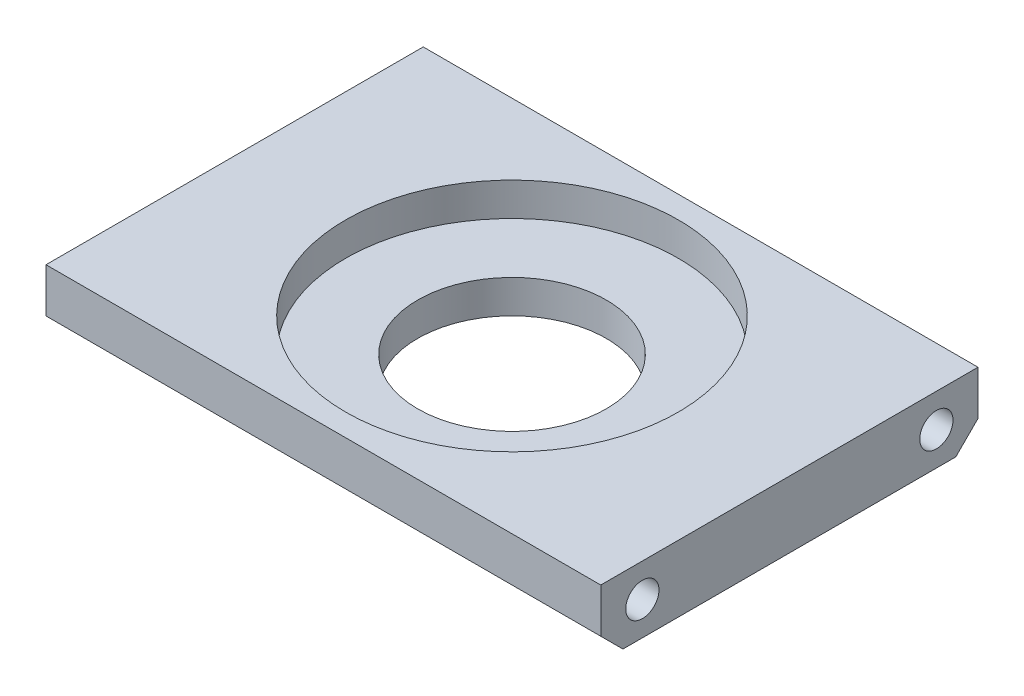
SolidWorks part; units mm, degrees
ref_plane "Front Plane" through (0, 0, 0) normal (0, 0, 1) x (1, 0, 0)
ref_plane "Top Plane" through (0, 0, 0) normal (0, 1, 0) x (1, 0, 0)
ref_plane "Right Plane" through (0, 0, 0) normal (1, 0, 0) x (0, 0, -1)
sketch "Sketch1" plane through (0, 0, 0) normal (0, 1, 0) x (1, 0, 0)
  line L1 (0, 0) -> (50, 0)
  line L2 (0, 0) -> (0, 34)
  line L3 (0, 34) -> (50, 34)
  line L4 (50, 0) -> (50, 34)
  dimension "D1" = 34
  dimension "D2" = 50
extrude "Boss-Extrude1" add sketch "Sketch1" along normal blind 6
sketch "Sketch2" plane through (50, 0, 0) normal (1, 0, 0) x (0, 0, -1)
  line L0 (0, 3) -> (3.75, 3) construction
  line L1 (0, 6) -> (0, 0) construction
  line L2 (34, 3) -> (30.25, 3) construction
  line L3 (34, 6) -> (34, 0) construction
  circle A0 centre (3.75, 3) radius 1.5
  circle A1 centre (30.25, 3) radius 1.5
  dimension "D1" = 3.75
  dimension "D2" = 3.75
extrude "Cut-Extrude1" cut sketch "Sketch2" against normal blind 7
sketch "Sketch3" plane through (0, 0, 0) normal (-1, 0, 0) x (0, 0, 1)
  line L0 (-34, 3) -> (-30.25, 3) construction
  line L1 (-34, 6) -> (-34, 0) construction
  line L2 (0, 3) -> (-3.75, 3) construction
  line L3 (0, 6) -> (0, 0) construction
  circle A0 centre (-30.25, 3) radius 1.5
  circle A1 centre (-3.75, 3) radius 1.5
  dimension "D1" = 3.75
  dimension "D2" = 3.75
extrude "Cut-Extrude2" cut sketch "Sketch3" against normal blind 7
chamfer "Chamfer2" distance 2 angle 45 2 edges at (25, 0, 0) (25, 0, -34)
sketch "Sketch4" plane through (0, 6, 0) normal (0, 1, 0) x (1, 0, 0)
  line L0 (25, 34) -> (25, 0) construction
  line L1 (50, 34) -> (0, 34) construction
  line L2 (0, 0) -> (50, 0) construction
  circle A0 centre (25, 17) radius 15
  dimension "D1" = 30
extrude "Cut-Extrude3" cut sketch "Sketch4" against normal blind 3
sketch "Sketch5" plane through (0, 3, 0) normal (0, 1, 0) x (1, 0, 0)
  circle A0 centre (25, 17) radius 8.5
extrude "Cut-Extrude4" cut sketch "Sketch5" against normal blind 3 contours A0
